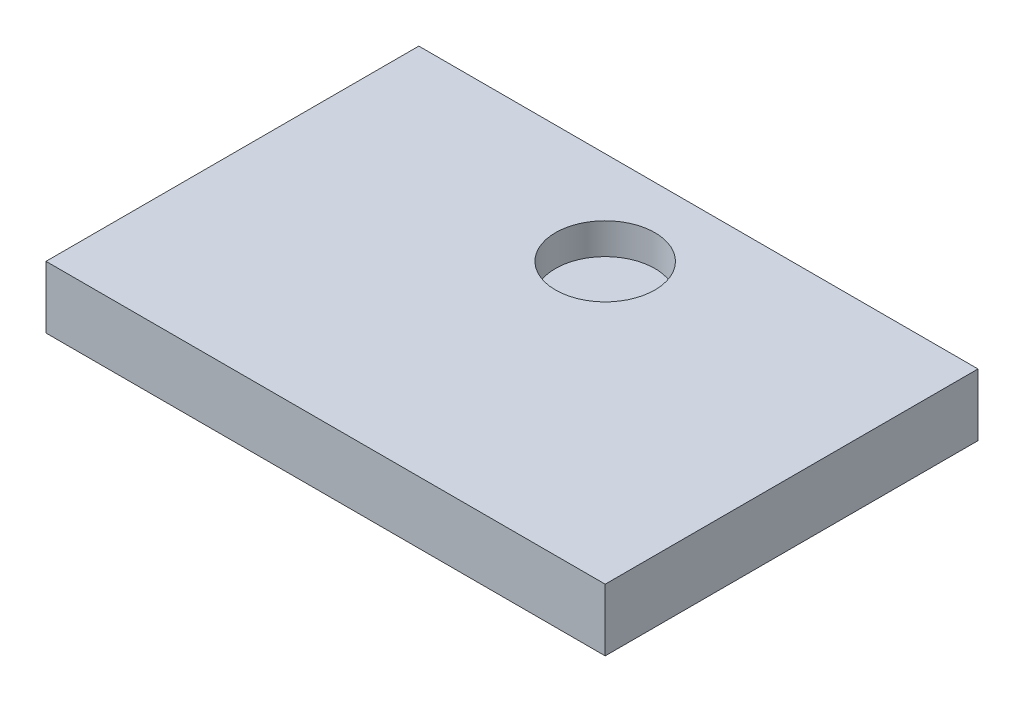
SolidWorks part; units mm, degrees
ref_plane "前视" through (0, 0, 0) normal (0, 0, 1) x (1, 0, 0)
ref_plane "上视" through (0, 0, 0) normal (0, 1, 0) x (1, 0, 0)
ref_plane "右视" through (0, 0, 0) normal (1, 0, 0) x (0, 0, -1)
sketch "Sketch1" plane through (0, 0, 0) normal (0, 1, 0) x (1, 0, 0)
  line L1 (0, 0) -> (90, 0)
  line L2 (0, 0) -> (0, 60)
  line L3 (0, 60) -> (90, 60)
  line L4 (90, 0) -> (90, 60)
  dimension "D1" = 90
  dimension "D2" = 60
extrude "Extrude1" add sketch "Sketch1" along normal blind 10
sketch "Sketch2" plane through (0, 10, 0) normal (0, 1, 0) x (1, 0, 0)
  line L0 (0, 0) -> (90, 0) construction
  circle A0 centre (45, 45) radius 8
  dimension "D1" = 45
extrude "Extrude2" cut sketch "Sketch2" against normal blind 5
